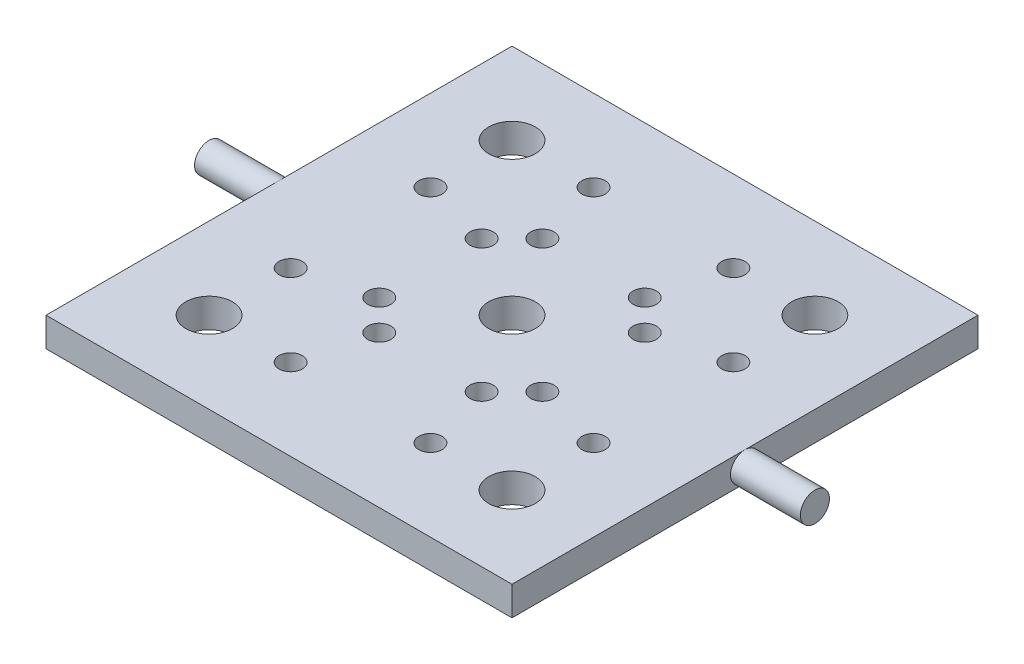
SolidWorks part; units mm, degrees
ref_plane "Front Plane" through (0, 0, 0) normal (0, 0, 1) x (1, 0, 0)
ref_plane "Top Plane" through (0, 0, 0) normal (0, 1, 0) x (1, 0, 0)
ref_plane "Right Plane" through (0, 0, 0) normal (1, 0, 0) x (0, 0, -1)
sketch "Sketch1" plane through (0, 0, 0) normal (0, 1, 0) x (1, 0, 0)
  line L1 (-25.4, -25.4) -> (25.4, -25.4)
  line L2 (-25.4, -25.4) -> (-25.4, 25.4)
  line L3 (-25.4, 25.4) -> (25.4, 25.4)
  line L4 (25.4, -25.4) -> (25.4, 25.4)
  line L5 (-25.4, -25.4) -> (25.4, 25.4) construction
  line L6 (-25.4, 25.4) -> (25.4, -25.4) construction
  point P0 (0, 0)
  dimension "D1" = 50.8
extrude "Boss-Extrude1" add sketch "Sketch1" along normal mid plane 3.175
sketch "Sketch3" plane through (25.4, 0, 0) normal (1, 0, 0) x (0, 0, -1)
  circle A0 centre (0, 0) radius 1.5875
extrude "Boss-Extrude2" add sketch "Sketch3" along normal blind 7.62
mirror "Mirror1" about plane through (0, 0, 0) normal (1, 0, 0) of "Boss-Extrude2"
sketch "Sketch4" plane through (0, 1.5875, 0) normal (0, 1, 0) x (1, 0, 0)
  line L0 (25.4, 25.4) -> (-25.4, 25.4) construction
  line L1 (-25.4, 25.4) -> (-25.4, 0) construction
  line L2 (25.4, 0) -> (25.4, 25.4) construction
  line L3 (25.4, -25.4) -> (25.4, 0) construction
  line L4 (-25.4, -25.4) -> (25.4, -25.4) construction
  line L5 (-25.4, 0) -> (-25.4, -25.4) construction
  line L6 (-25.4, 0) -> (25.4, 0) construction
  line L7 (0, 25.4) -> (0, -25.4) construction
  line L8 (-7.62, 16.51) -> (-7.62, 0) construction
  line L9 (-7.62, 16.51) -> (5.5782, 8.89) construction
  line L10 (7.62, 16.51) -> (7.62, 0) construction
  line L11 (-5.5782, 8.89) -> (7.62, 16.51) construction
  circle A0 centre (0, 0) radius 2.54
  circle A1 centre (-16.51, 16.51) radius 2.54
  circle A2 centre (16.51, 16.51) radius 2.54
  circle A3 centre (16.51, -16.51) radius 2.54
  circle A4 centre (-16.51, -16.51) radius 2.54
  circle A5 centre (-16.51, 7.62) radius 1.27
  circle A6 centre (-7.62, 16.51) radius 1.27
  circle A7 centre (7.62, 16.51) radius 1.27
  circle A14 centre (-16.51, -7.62) radius 1.27
  circle A17 centre (7.62, -16.51) radius 1.27
  circle A18 centre (-7.62, -16.51) radius 1.27
  circle A19 centre (16.51, -7.62) radius 1.27
  circle A20 centre (16.51, 7.62) radius 1.27
  circle A21 centre (5.5782, 8.89) radius 1.27
  circle A22 centre (-5.5782, 8.89) radius 1.27
  circle A23 centre (8.89, -5.5782) radius 1.27
  circle A24 centre (8.89, 5.5782) radius 1.27
  circle A25 centre (-5.5782, -8.89) radius 1.27
  circle A26 centre (5.5782, -8.89) radius 1.27
  circle A27 centre (-8.89, 5.5782) radius 1.27
  circle A28 centre (-8.89, -5.5782) radius 1.27
  point P66 (0, 0)
  dimension "D1" = 5.08
  dimension "D2" = 2.54
  dimension "D3" = 8.89
  dimension "D4" = 8.89
  dimension "D5" = 8.89
  dimension "D6" = 8.89
  dimension "D7" = 8.89
  dimension "D8" = 8.89
  dimension "D9" = 8.89
  dimension "D10" = 8.89
  dimension "D11" = 15.24
  dimension "D12" = 15.24
  dimension "D13" = 15.24
  dimension "D14" = 8.89
  dimension "D15" = 8.89
  dimension "D16" = 60
  dimension "D17" = 15.24
  dimension "D18" = 60
  dimension "D19" = 4
extrude "Cut-Extrude1" cut sketch "Sketch4" against normal through all
